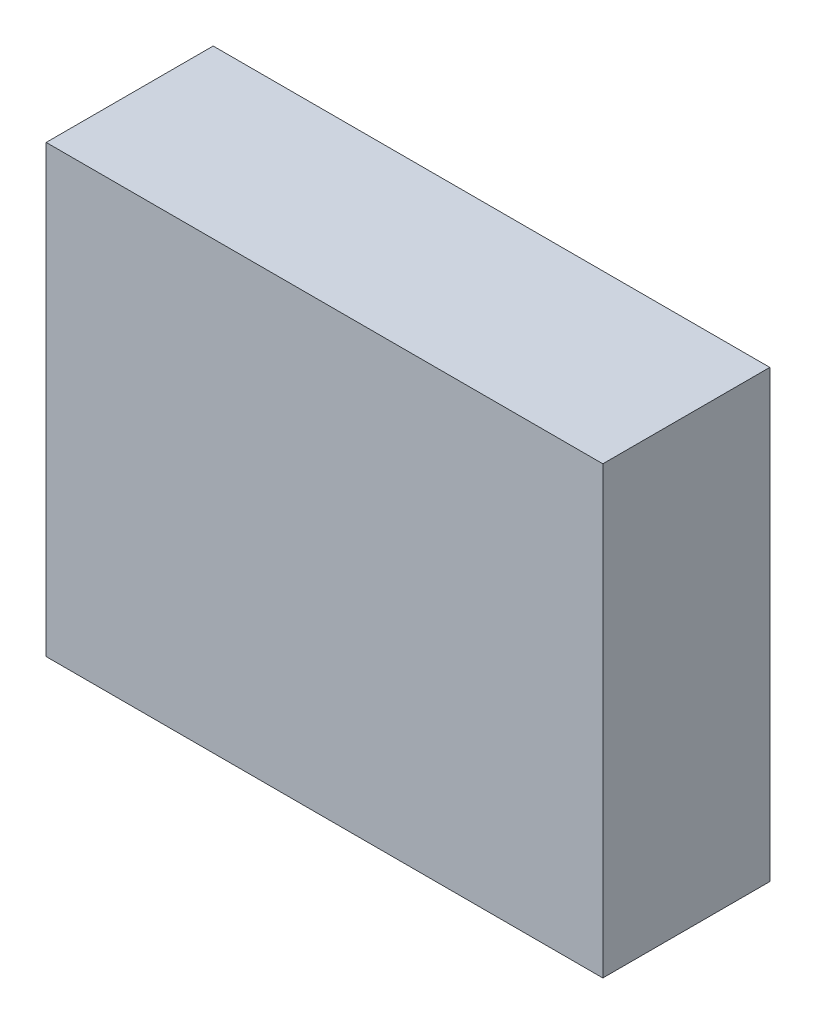
SolidWorks part; units mm, degrees
ref_plane "Front Plane" through (0, 0, 0) normal (0, 0, 1) x (1, 0, 0)
ref_plane "Top Plane" through (0, 0, 0) normal (0, 1, 0) x (1, 0, 0)
ref_plane "Right Plane" through (0, 0, 0) normal (1, 0, 0) x (0, 0, -1)
sketch "Sketch1" plane through (0, 0, 0) normal (0, 0, 1) x (1, 0, 0)
  line L1 (-15.875, -12.7) -> (15.875, -12.7)
  line L2 (-15.875, -12.7) -> (-15.875, 12.7)
  line L3 (-15.875, 12.7) -> (15.875, 12.7)
  line L4 (15.875, -12.7) -> (15.875, 12.7)
  line L5 (-15.875, -12.7) -> (15.875, 12.7) construction
  line L6 (-15.875, 12.7) -> (15.875, -12.7) construction
  point P0 (0, 0)
  dimension "D1" = 25.4
  dimension "D2" = 31.75
extrude "Boss-Extrude1" add sketch "Sketch1" along normal blind 9.525
